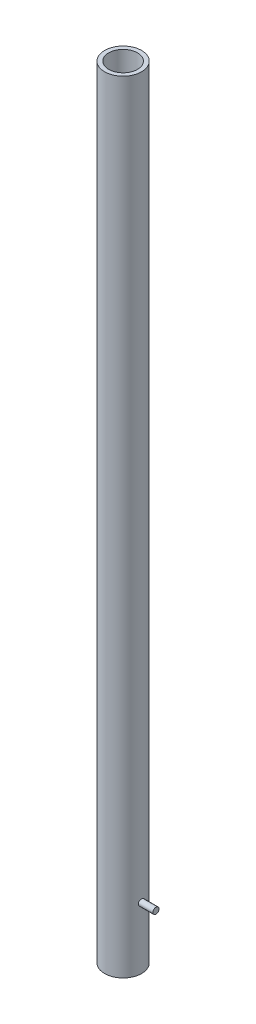
SolidWorks part; units mm, degrees
ref_plane "Front Plane" through (0, 0, 0) normal (0, 0, 1) x (1, 0, 0)
ref_plane "Top Plane" through (0, 0, 0) normal (0, 1, 0) x (1, 0, 0)
ref_plane "Right Plane" through (0, 0, 0) normal (1, 0, 0) x (0, 0, -1)
sketch "Sketch1" plane through (0, 0, 0) normal (0, 1, 0) x (1, 0, 0)
  circle A0 centre (0, 0) radius 7
  dimension "D1" = 14
extrude "Extrude-Thin1" add sketch "Sketch1" along normal blind 380 thin
sketch "Sketch2" plane through (0, 0, 0) normal (1, 0, 0) x (0, 0, -1)
  circle A0 centre (0, 4.5) radius 1.5
  dimension "D2" = 3
  dimension "D1" = 4.5
extrude "Boss-Extrude1" add sketch "Sketch2" along normal up to next and the other way up to next
sketch "Sketch3" plane through (0, 0, 0) normal (1, 0, 0) x (0, 0, -1)
  circle A0 centre (0, 30) radius 1.5
  dimension "D1" = 3
  dimension "D2" = 30
extrude "Boss-Extrude2" add sketch "Sketch3" along normal blind 8 from offset 8
